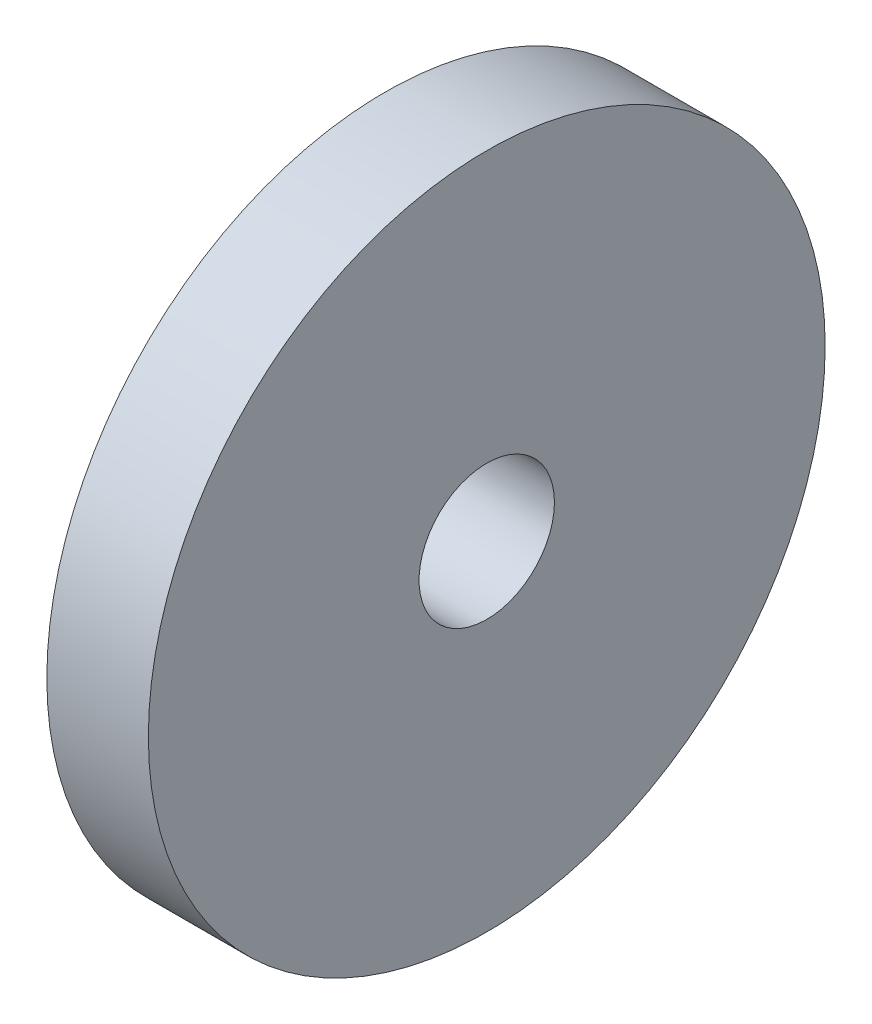
SolidWorks part; units mm, degrees
ref_plane "前视基准面" through (0, 0, 0) normal (0, 0, 1) x (1, 0, 0)
ref_plane "上视基准面" through (0, 0, 0) normal (0, 1, 0) x (1, 0, 0)
ref_plane "右视基准面" through (0, 0, 0) normal (1, 0, 0) x (0, 0, -1)
other "Configuration Table"
sketch "草图1" plane through (0, 0, 0) normal (1, 0, 0) x (0, 0, -1)
  circle A0 centre (0, 0) radius 10
  dimension "D1" = 20
extrude "凸台-拉伸1" add sketch "草图1" along normal blind 3
sketch "草图2" plane through (3, 0, 0) normal (1, 0, 0) x (0, 0, -1)
  circle A0 centre (0, 0) radius 2
  dimension "D1" = 4
extrude "切除-拉伸1" cut sketch "草图2" against normal blind 3
